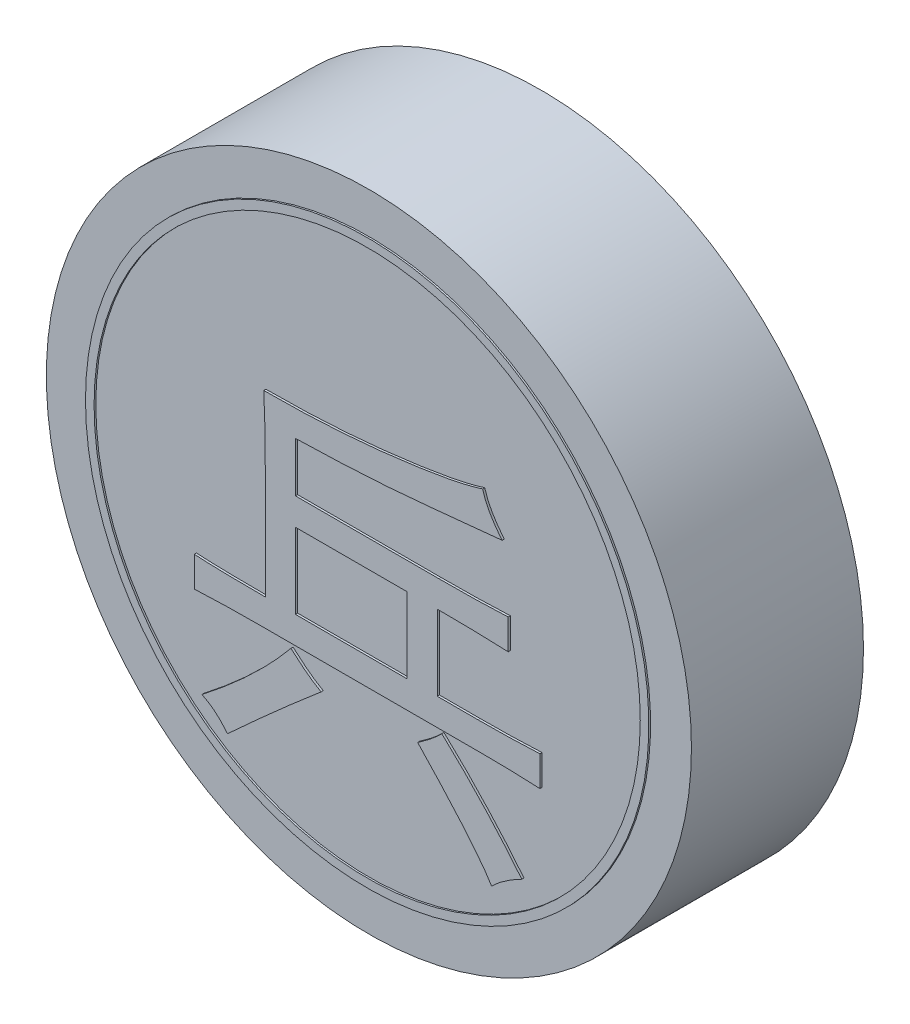
SolidWorks part; units mm, degrees
ref_plane "前视基准面" through (0, 0, 0) normal (0, 0, 1) x (1, 0, 0)
ref_plane "上视基准面" through (0, 0, 0) normal (0, 1, 0) x (1, 0, 0)
ref_plane "右视基准面" through (0, 0, 0) normal (1, 0, 0) x (0, 0, -1)
other "Configuration Table"
sketch "草图1" plane through (0, 0, 0) normal (0, 0, 1) x (1, 0, 0)
  circle A0 centre (0, 0) radius 15
  dimension "D1" = 30
extrude "Diameter30_Height8" add sketch "草图1" against normal blind 8
sketch "草图2" plane through (0, 0, 0) normal (0, 0, 1) x (1, 0, 0)
  text T0 "兵" font "SimHei" height 12
extrude "Character_兵" add sketch "草图2" along normal blind 0.1
sketch "草图3" plane through (0, 0, 0) normal (0, 0, 1) x (1, 0, 0)
  circle A0 centre (0, 0) radius 13.1
  circle A1 centre (0, 0) radius 12.7
extrude "Ink_ring" add sketch "草图3" along normal blind 0.08
